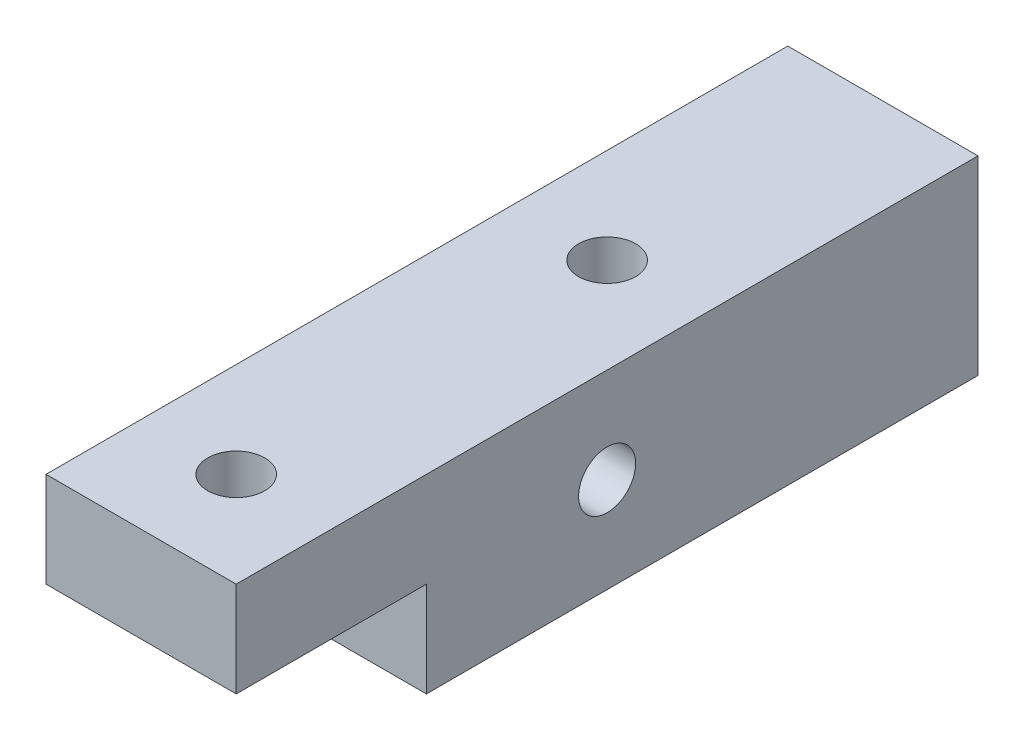
SolidWorks part; units mm, degrees
ref_plane "Plan de face" through (0, 0, 0) normal (0, 0, 1) x (1, 0, 0)
ref_plane "Plan de dessus" through (0, 0, 0) normal (0, 1, 0) x (1, 0, 0)
ref_plane "Plan de droite" through (0, 0, 0) normal (1, 0, 0) x (0, 0, -1)
sketch "Esquisse1" plane through (0, 0, 0) normal (0, 0, 1) x (1, 0, 0)
  line L1 (0, 0) -> (10, 0)
  line L2 (0, 0) -> (0, 10)
  line L3 (0, 10) -> (10, 10)
  line L4 (10, 0) -> (10, 10)
  dimension "D1" = 10
  dimension "D2" = 10
extrude "Boss.-Extru.1" add sketch "Esquisse1" along normal blind 39
sketch "Esquisse2" plane through (0, 0, 0) normal (-1, 0, 0) x (0, 0, 1)
  line L0 (39, 0) -> (0, 0) construction
  line L1 (29, 0) -> (39, 0)
  line L2 (29, 0) -> (29, 5)
  line L3 (29, 5) -> (39, 5)
  line L4 (39, 0) -> (39, 5)
  line L5 (39, 10) -> (39, 0) construction
  line L6 (39, 10) -> (0, 10) construction
  dimension "D1" = 10
  dimension "D2" = 5
extrude "Enlèv. mat.-Extru.1" cut sketch "Esquisse2" against normal blind 10
sketch "Esquisse3" plane through (0, 0, 0) normal (0, 0, -1) x (-1, 0, 0)
  line L0 (-10, 10) -> (0, 10) construction
  line L1 (0, 10) -> (0, 0) construction
  circle A0 centre (-5, 5) radius 1.5
  dimension "D1" = 5
  dimension "D2" = 5
  dimension "D3" = 3
extrude "Enlèv. mat.-Extru.2" cut sketch "Esquisse3" against normal blind 10
sketch "Esquisse4" plane through (0, 10, 0) normal (0, 1, 0) x (1, 0, 0)
  line L0 (0, -39) -> (0, 0) construction
  line L1 (10, -39) -> (0, -39) construction
  circle A0 centre (5, -34) radius 1.5
  dimension "D1" = 3
  dimension "D2" = 5
  dimension "D3" = 5
extrude "Enlèv. mat.-Extru.3" cut sketch "Esquisse4" against normal through all
sketch "Esquisse5" plane through (0, 0, 0) normal (-1, 0, 0) x (0, 0, 1)
  line L0 (39, 10) -> (0, 10) construction
  line L1 (0, 10) -> (0, 0) construction
  circle A0 centre (19.5, 5) radius 1.5
  point P6 (0, 5)
  dimension "D1" = 3
  dimension "D2" = 5
  dimension "D3" = 19.5
extrude "Enlèv. mat.-Extru.4" cut sketch "Esquisse5" against normal through all
sketch "Esquisse6" plane through (0, 10, 0) normal (0, 1, 0) x (1, 0, 0)
  line L0 (10, -39) -> (10, 0) construction
  line L1 (10, 0) -> (0, 0) construction
  circle A0 centre (5, -14.5) radius 1.5
  dimension "D1" = 3
  dimension "D2" = 5
  dimension "D3" = 14.5
extrude "Enlèv. mat.-Extru.5" cut sketch "Esquisse6" against normal through all
